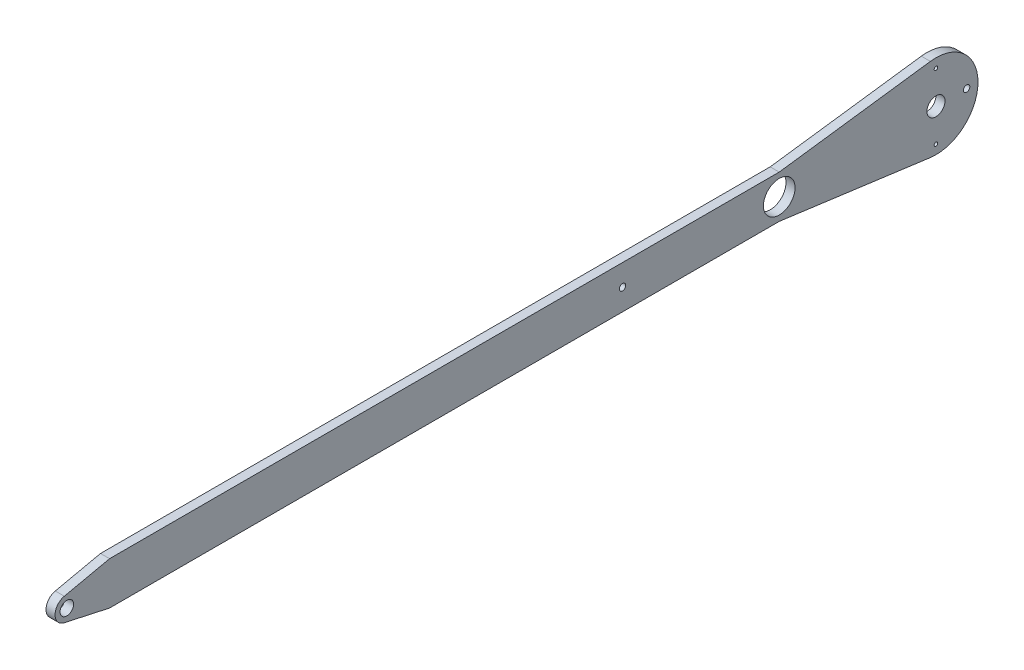
SolidWorks part; units mm, degrees
ref_plane "Front Plane" through (0, 0, 0) normal (0, 0, 1) x (1, 0, 0)
ref_plane "Top Plane" through (0, 0, 0) normal (0, 1, 0) x (1, 0, 0)
ref_plane "Right Plane" through (0, 0, 0) normal (1, 0, 0) x (0, 0, -1)
sketch "Sketch1" plane through (0, 0, 0) normal (1, 0, 0) x (0, 0, -1)
  line L0 (-470, 15) -> (-501.7607, 8.0727)
  line L1 (-470, 15) -> (0, 15)
  line L2 (-470, 15) -> (-470, -15) construction
  line L3 (-470, -15) -> (0, -15)
  line L4 (0, 15) -> (0, 11.1125) construction
  line L5 (-470, -15) -> (-501.7607, -8.0727)
  line L6 (0, 11.1125) -> (0, -11.1125) construction
  line L7 (0, -11.1125) -> (0, -15) construction
  line L8 (0, 15) -> (106.0756, 29.2378)
  line L9 (0, -15) -> (106.0756, -29.2378)
  circle A0 centre (110, 0) radius 6.35
  circle A1 centre (0, 0) radius 11.1125
  circle A2 centre (-500, 0) radius 4.7625
  arc A3 (106.0756, -29.2378) -> (106.0756, 29.2378) centre (110, 0) ccw
  arc A4 (-501.7607, 8.0727) -> (-501.7607, -8.0727) centre (-500, 0) ccw
  arc A5 (-501.7607, -8.0727) -> (-501.7607, 8.0727) centre (-500, 0) ccw construction
  arc A6 (106.0756, 29.2378) -> (106.0756, -29.2378) centre (110, 0) ccw construction
  point P13 (-470, 0)
  dimension "D3" = 22.225
  dimension "D4" = 9.525
  dimension "D5" = 12.7
  dimension "D6" = 59
  dimension "D7" = 3.5
  dimension "D1" = 500
  dimension "D2" = 110
  dimension "D8" = 30
  dimension "D9" = 30
extrude "Boss-Extrude1" add sketch "Sketch1" along normal mid plane 6.35
hole_wizard "M3x0.5 Tapped Hole1" positions "Sketch2" profile "Sketch3" tap size "M3x0.5" standard "ANSI Metric" end condition through all
sketch "Sketch2" plane through (3.175, 0, 0) normal (1, 0, 0) x (0, 0, -1)
  line L0 (110, -23.015) -> (110, 23.015)
  line L2 (55, 0) -> (-55, 0) construction
  circle A0 centre (110, 0) radius 6.35 construction
  point P0 (110, 23.015)
  point P12 (110, 0)
  point P13 (110, -23.015)
  dimension "D1" = 23.015
sketch "Sketch3" plane through (3.175, 23.015, -110) normal (0, 1, 0) x (0, 0, -1)
  line L0 (0, 0) -> (0, 6.35)
  line L1 (0, 6.35) -> (1.25, 6.35)
  line L2 (1.25, 6.35) -> (1.25, 0)
  line L5 (1.25, 0) -> (0, 0)
  line L11 (0, -6.35) -> (0, 107.95) construction
  dimension "Thru Tap Drill Dia." = 2.5
  dimension "Thru Tap Drill Depth" = 6.35
cosmetic thread "Hole Thread1"
cosmetic thread "Hole Thread2"
hole_wizard "M4 Clearance Hole1" positions "Sketch4" profile "Sketch5" hole size "M4" standard "ANSI Metric" end condition through all
sketch "Sketch4" plane through (3.175, 0, 0) normal (1, 0, 0) x (0, 0, -1)
  circle A0 centre (110, 0) radius 6.35 construction
  circle A1 centre (110, 0) radius 6.35
  point P0 (131.5, 0)
  point P6 (-110, 0)
  point P8 (0, 0)
  dimension "D1" = 21.5
  dimension "D2" = 110
sketch "Sketch5" plane through (3.175, 0, -131.5) normal (0, 1, 0) x (0, 0, -1)
  line L0 (0, 0) -> (0, 6.35)
  line L1 (0, 6.35) -> (2.25, 6.35)
  line L2 (2.25, 6.35) -> (2.25, 0)
  line L5 (2.25, 0) -> (0, 0)
  line L11 (0, -6.35) -> (0, 107.95) construction
  dimension "Thru Hole Dia." = 4.5
  dimension "Thru Hole Depth" = 6.35
